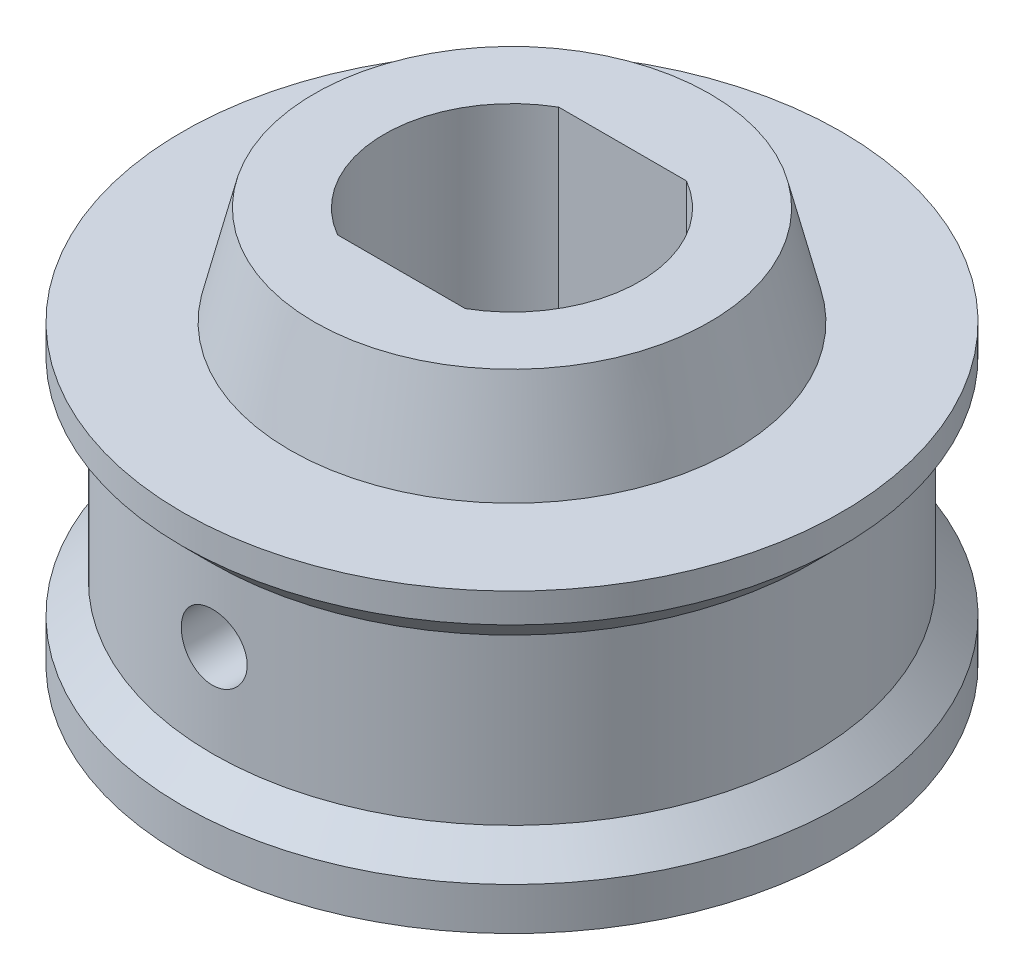
SolidWorks part; units mm, degrees
ref_plane "Front Plane" through (0, 0, 0) normal (0, 0, 1) x (1, 0, 0)
ref_plane "Top Plane" through (0, 0, 0) normal (0, 1, 0) x (1, 0, 0)
ref_plane "Right Plane" through (0, 0, 0) normal (1, 0, 0) x (0, 0, -1)
sketch "Sketch4" plane through (0, 0, 0) normal (0, 0, 1) x (1, 0, 0)
  line L0 (0, 0) -> (10, 0)
  line L1 (10, 0) -> (10, 1.2894)
  line L2 (10, 1.2894) -> (9.09, 2.1994)
  line L3 (9.09, 2.1994) -> (9.09, 7.1994)
  line L4 (9.09, 7.1994) -> (10, 8.1093)
  line L5 (10, 8.1093) -> (10, 9)
  line L6 (10, 9) -> (6.7356, 9)
  line L7 (0, 9) -> (0, 0)
  line L8 (0, 9) -> (0, 12)
  line L9 (0, 12) -> (6, 12)
  line L10 (6, 12) -> (6.7356, 9)
  line L11 (6.7356, 9) -> (0, 9) construction
  dimension "D1" = 10
  dimension "D2" = 45
  dimension "D3" = 6
  dimension "D4" = 5
  dimension "D5" = 9
  dimension "D6" = 3
  dimension "D7" = 45
revolve "Revolve1" add sketch "Sketch4" angle 360 about L7
sketch "Sketch5" plane through (0, 12, 0) normal (0, 1, 0) x (1, 0, 0)
  line L1 (3.875, 0) -> (1.9375, 3.3558) construction
  line L2 (1.9375, 3.3558) -> (-1.9375, 3.3558)
  line L3 (-1.9375, 3.3558) -> (-3.875, 0) construction
  line L4 (-3.875, 0) -> (-1.9375, -3.3558) construction
  line L5 (-1.9375, -3.3558) -> (1.9375, -3.3558)
  line L6 (1.9375, -3.3558) -> (3.875, 0) construction
  arc A0 (-1.9375, 3.3558) -> (-1.9375, -3.3558) centre (0, 0) ccw
  arc A1 (1.9375, -3.3558) -> (1.9375, 3.3558) centre (0, 0) ccw
  dimension "D1" = 7.75
extrude "Cut-Extrude1" cut sketch "Sketch5" against normal blind 21
sketch "Sketch6" plane through (0, 0, 0) normal (0, 0, 1) x (1, 0, 0)
  circle A0 centre (0, 5) radius 1
  dimension "D1" = 2
  dimension "D2" = 5
extrude "Cut-Extrude2" cut sketch "Sketch6" against normal through all both and the other way through all
